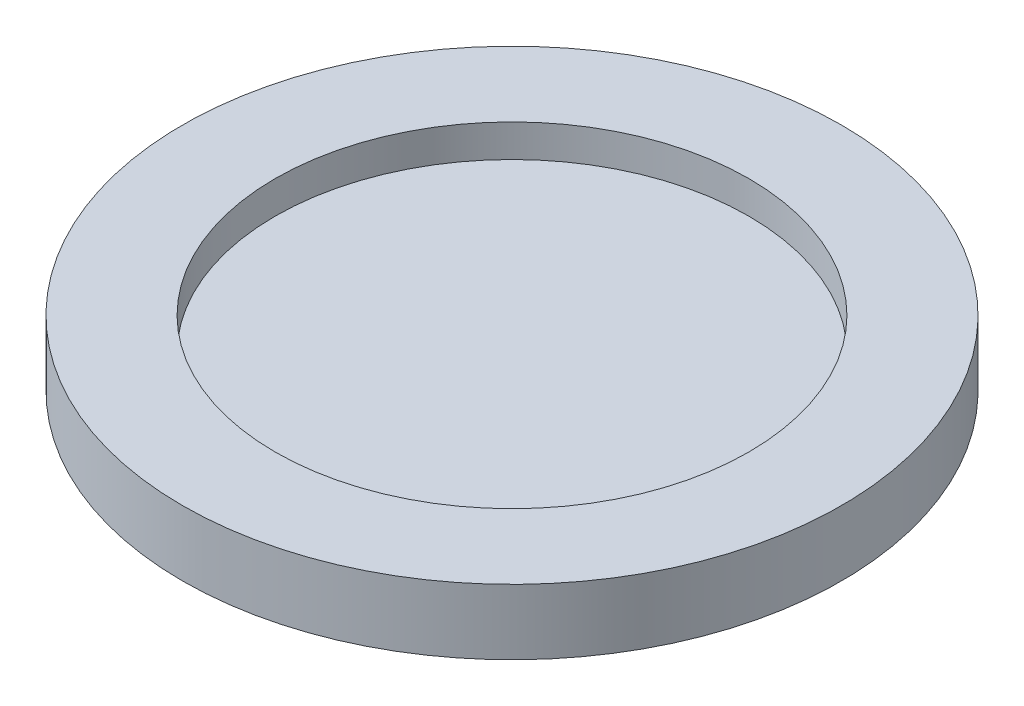
SolidWorks part; units mm, degrees
material "Rubber"
ref_plane "Front Plane" through (0, 0, 0) normal (0, 0, 1) x (1, 0, 0)
ref_plane "Top Plane" through (0, 0, 0) normal (0, 1, 0) x (1, 0, 0)
ref_plane "Right Plane" through (0, 0, 0) normal (1, 0, 0) x (0, 0, -1)
sketch "Sketch1" plane through (0, 0, 0) normal (0, 1, 0) x (1, 0, 0)
  circle A0 centre (0, 0) radius 9.7663
  circle A1 centre (0, 0) radius 13.589
  dimension "D1" = 19.5326
  dimension "D2" = 27.178
extrude "Boss-Extrude1" add sketch "Sketch1" along normal blind 2.6924
sketch "Sketch3" plane through (0, 0, 0) normal (0, 1, 0) x (1, 0, 0)
  circle A0 centre (0, 0) radius 9.7663
extrude "Boss-Extrude2" add sketch "Sketch3" along normal blind 1.35
sketch "Sketch4" plane through (0, 0, 0) normal (0, -1, 0) x (1, 0, 0)
  circle A0 centre (0, 0) radius 9.7663
extrude "Cut-Extrude1" cut sketch "Sketch4" against normal blind 1.25
